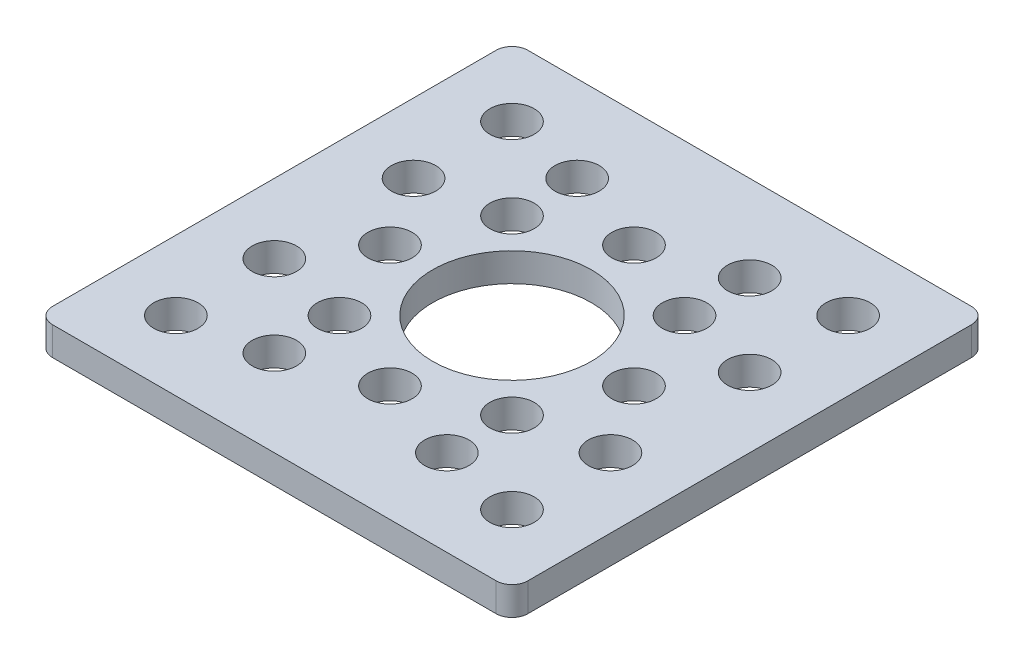
SolidWorks part; units mm, degrees
ref_plane "Front Plane" through (0, 0, 0) normal (0, 0, 1) x (1, 0, 0)
ref_plane "Top Plane" through (0, 0, 0) normal (0, 1, 0) x (1, 0, 0)
ref_plane "Right Plane" through (0, 0, 0) normal (1, 0, 0) x (0, 0, -1)
ref_plane "Plane1" through (0, 0, 0) normal (0, -1, 0) x (1, 0, 0)
sketch "Sketch1" plane through (0, 0, 0) normal (0, -1, 0) x (1, 0, 0)
  line L0 (-17.78, -19.05) -> (17.78, -19.05)
  line L1 (19.05, -17.78) -> (19.05, 17.78)
  line L2 (17.78, 19.05) -> (-17.78, 19.05)
  line L3 (-19.05, 17.78) -> (-19.05, -17.78)
  circle A0 centre (-13.4704, 13.4704) radius 1.778
  circle A1 centre (-13.4704, 5.5796) radius 1.778
  circle A2 centre (-6.9148, -12.1352) radius 1.778
  circle A3 centre (13.4704, -13.4704) radius 1.778
  circle A4 centre (6.9148, 6.9148) radius 1.778
  arc A5 (17.78, -19.05) -> (19.05, -17.78) centre (17.78, -17.78) ccw
  arc A6 (19.05, 17.78) -> (17.78, 19.05) centre (17.78, 17.78) ccw
  arc A7 (-17.78, 19.05) -> (-19.05, 17.78) centre (-17.78, 17.78) ccw
  arc A8 (-19.05, -17.78) -> (-17.78, -19.05) centre (-17.78, -17.78) ccw
  circle A9 centre (0, 0) radius 6.3627
  circle A10 centre (9.779, 0) radius 1.778
  circle A11 centre (6.9148, -6.9148) radius 1.778
  circle A12 centre (0, -9.779) radius 1.778
  circle A13 centre (-6.9148, -6.9148) radius 1.778
  circle A14 centre (-9.779, 0) radius 1.778
  circle A15 centre (-6.9148, 6.9148) radius 1.778
  circle A16 centre (0, 9.779) radius 1.778
  circle A17 centre (13.4704, 5.5796) radius 1.778
  circle A18 centre (6.9148, 12.1352) radius 1.778
  circle A19 centre (13.4704, 13.4704) radius 1.778
  circle A20 centre (13.4704, -5.5796) radius 1.778
  circle A21 centre (6.9148, -12.1352) radius 1.778
  circle A22 centre (-13.4704, -5.5796) radius 1.778
  circle A23 centre (-13.4704, -13.4704) radius 1.778
  circle A24 centre (-6.9148, 12.1352) radius 1.778
extrude "Boss-Extrude1" add sketch "Sketch1" against normal blind 2.286
